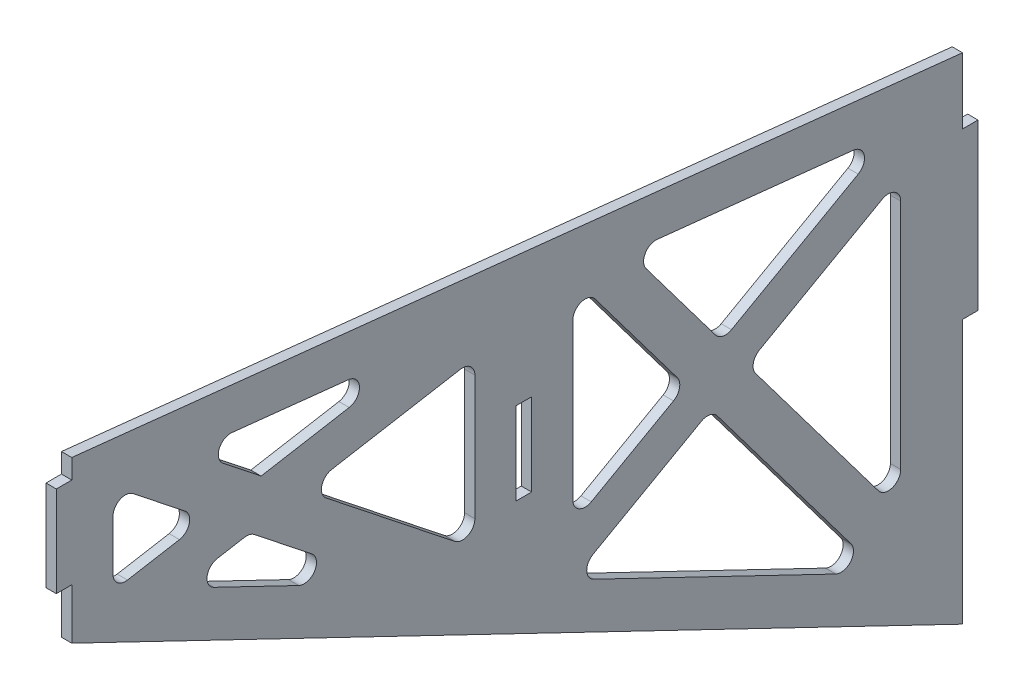
SolidWorks part; units mm, degrees
material "Balsa"
ref_plane "Front Plane" through (0, 0, 0) normal (0, 0, 1) x (1, 0, 0)
ref_plane "Top Plane" through (0, 0, 0) normal (0, 1, 0) x (1, 0, 0)
ref_plane "Right Plane" through (0, 0, 0) normal (1, 0, 0) x (0, 0, -1)
sketch "Sketch3" plane through (0, 0, 0) normal (1, 0, 0) x (0, 0, -1)
  line L0 (0, 0) -> (274.32, 0)
  line L10 (0, -20.32) -> (0, -4.737)
  line L11 (0, -4.737) -> (-4.7625, -4.737)
  line L12 (-4.7625, -4.737) -> (-4.7625, -2.197)
  line L13 (-4.7625, -2.197) -> (0, -2.197)
  line L14 (0, -2.197) -> (0, 0)
  line L15 (0, -20.32) -> (274.32, -152.4)
  line L18 (274.32, -20.32) -> (279.0825, -20.32)
  line L19 (279.0825, -20.32) -> (279.0825, -71.12)
  line L20 (279.0825, -71.12) -> (274.32, -71.12)
  line L21 (274.32, -71.12) -> (274.32, -152.4)
  line L22 (274.32, 0) -> (274.32, -20.32)
  dimension "D1" = 4.7625
  dimension "D2" = 2.54
  dimension "D4" = 274.32
  dimension "D5" = 152.4
  dimension "D6" = 20.32
  dimension "D7" = 50.8
  dimension "D8" = 4.7625
extrude "Boss-Extrude1" add sketch "Sketch3" along normal blind 3.175
sketch "Sketch4" plane through (3.175, 0, 0) normal (1, 0, 0) x (0, 0, -1)
  line L0 (136.8425, -25.4) -> (136.8425, -50.8)
  line L1 (136.8425, -50.8) -> (141.605, -50.8)
  line L2 (141.605, -50.8) -> (141.605, -25.4)
  line L3 (141.605, -25.4) -> (136.8425, -25.4)
  line L4 (279.0825, -71.12) -> (279.0825, -20.32) construction
  line L5 (274.32, 0) -> (0, 0) construction
  dimension "D1" = 142.24
  dimension "D2" = 25.4
  dimension "D3" = 25.4
  dimension "D4" = 4.7625
extrude "Cut-Extrude1" cut sketch "Sketch4" against normal through all
sketch "Sketch7" plane through (3.175, 0, 0) normal (1, 0, 0) x (0, 0, -1)
  line L0 (0, 0) -> (274.32, 0)
  line L3 (0, 29.21) -> (0, 0)
  line L4 (0, 29.21) -> (274.32, 0)
extrude "Boss-Extrude2" add sketch "Sketch7" against normal blind 3.175
sketch "Sketch8" plane through (3.175, 0, 0) normal (1, 0, 0) x (0, 0, -1)
  line L0 (-4.7625, -2.197) -> (0, -2.197)
  line L1 (0, -2.197) -> (0, 23.203)
  line L3 (0, 23.203) -> (-4.7625, 23.203)
  line L4 (-4.7625, 23.203) -> (-4.7625, -2.197)
  dimension "D1" = 25.4
extrude "Boss-Extrude3" add sketch "Sketch8" against normal blind 3.175
sketch "Sketch9" plane through (3.175, 0, 0) normal (1, 0, 0) x (0, 0, -1)
  line L0 (36.259, 12.5773) -> (112.244, 4.4863)
  line L1 (112.244, 4.4863) -> (58.3095, -4.8923)
  line L2 (58.3095, -4.8923) -> (36.259, 12.5773)
  line L3 (12.7, -12.8232) -> (12.7, 15.0393)
  line L4 (12.7, 15.0393) -> (41.539, -7.8085)
  line L5 (41.539, -7.8085) -> (12.7, -12.8232)
  line L6 (33.1074, -22.1652) -> (54.8814, -18.379)
  line L7 (54.8814, -18.379) -> (100.7993, -54.7576)
  line L8 (100.7993, -54.7576) -> (33.1074, -22.1652)
  line L9 (71.6519, -15.4628) -> (124.1425, -6.3353)
  line L10 (124.1425, -6.3353) -> (124.1425, -57.0486)
  line L11 (124.1425, -57.0486) -> (71.6519, -15.4628)
  line L12 (171.5866, -1.8326) -> (252.5652, -10.4553)
  line L13 (252.5652, -10.4553) -> (200.2566, -39.9174)
  line L14 (200.2566, -39.9174) -> (171.5866, -1.8326)
  line L15 (154.305, 0.0076) -> (154.305, -65.7989)
  line L16 (154.305, -65.7989) -> (189.0934, -46.2049)
  line L17 (189.0934, -46.2049) -> (154.305, 0.0076)
  line L18 (136.8425, -25.4) -> (136.8425, -50.8) construction
  line L19 (196.7989, -56.4408) -> (154.1664, -80.4529)
  line L20 (154.1664, -80.4529) -> (249.389, -126.3008)
  line L21 (249.389, -126.3008) -> (196.7989, -56.4408)
  line L22 (207.9621, -50.1533) -> (255.27, -23.5078)
  line L23 (255.27, -23.5078) -> (255.27, -112.9965)
  line L24 (255.27, -112.9965) -> (207.9621, -50.1533)
  line L25 (141.605, -50.8) -> (141.605, -25.4) construction
  line L26 (0, -4.737) -> (0, -20.32) construction
  line L27 (274.32, 0) -> (0, 29.21) construction
  line L28 (0, -20.32) -> (274.32, -152.4) construction
  line L29 (-4.7625, 23.203) -> (-4.7625, -4.737) construction
  line L30 (274.32, -152.4) -> (274.32, -71.12) construction
  dimension "D1" = 19.05
  dimension "D2" = 12.7
  dimension "D3" = 12.7
  dimension "D4" = 12.7
  dimension "D5" = 12.7
  dimension "D6" = 12.7
  dimension "D7" = 12.7
  dimension "D8" = 12.7
  dimension "D9" = 12.7
  dimension "D10" = 12.7
  dimension "D11" = 12.7
  dimension "D12" = 27.4506
  dimension "D13" = 22.0505
  dimension "D14" = 53.9345
  dimension "D15" = 21.7739
  dimension "D16" = 19.594
  dimension "D17" = 46.2125
  dimension "D18" = 28.67
extrude "Cut-Extrude2" cut sketch "Sketch9" against normal up to surface (3.175 mm away) contours L5 L3 L4 | L2 L0 L1 | L8 L6 L7 | L11 L9 L10 | L15 L16 L17 | L14 L12 L13 | L24 L22 L23 | L19 L20 L21 up to face at (0, -24.1215, -137.16)
fillet "Fillet1" radius 3.81 23 edges at (1.5875, -23.5078, -255.27) (1.5875, -50.1533, -207.9621) (1.5875, -112.9965, -255.27) (1.5875, -126.3008, -249.389) (1.5875, -10.4553, -252.5652) (1.5875, -46.2049, -189.0934) (1.5875, -65.7989, -154.305) (1.5875, -39.9174, -200.2566) (1.5875, -56.4408, -196.7989) (1.5875, 0.0076, -154.305) (1.5875, -6.3353, -124.1425) (1.5875, 4.4863, -112.244) (1.5875, -57.0486, -124.1425) (1.5875, -80.4529, -154.1664) (1.5875, -1.8326, -171.5866) (1.5875, -15.4628, -71.6519) (1.5875, 12.5773, -36.259) (1.5875, -18.379, -54.8814) (1.5875, -22.1652, -33.1074) (1.5875, -12.8232, -12.7) (1.5875, -54.7576, -100.7993) (1.5875, -7.8085, -41.539) (1.5875, 15.0393, -12.7)
